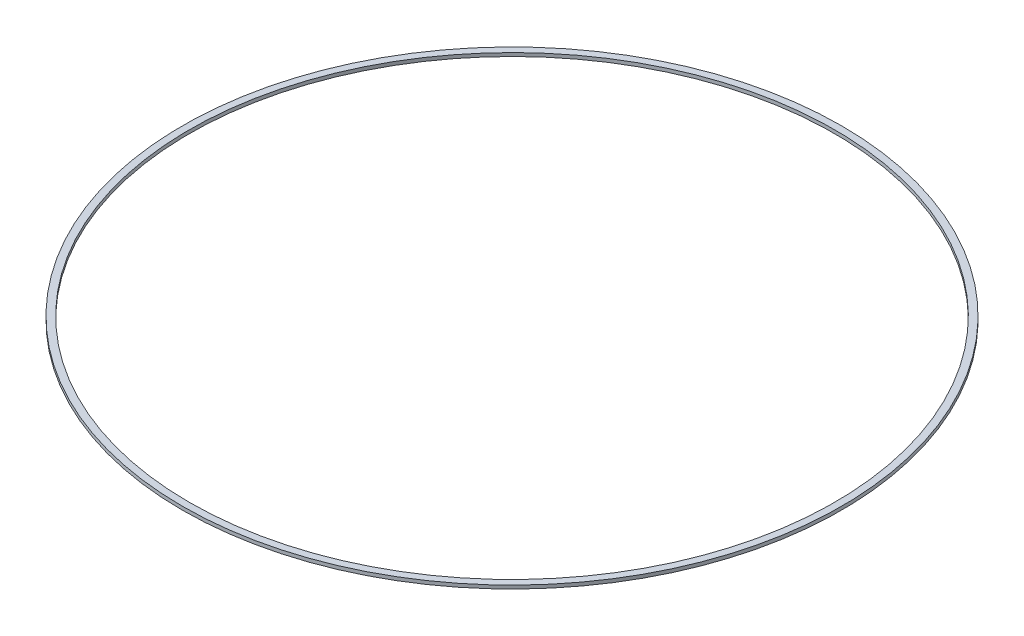
SolidWorks part; units mm, degrees
ref_plane "Front Plane" through (0, 0, 0) normal (0, 0, 1) x (1, 0, 0)
ref_plane "Top Plane" through (0, 0, 0) normal (0, 1, 0) x (1, 0, 0)
ref_plane "Right Plane" through (0, 0, 0) normal (1, 0, 0) x (0, 0, -1)
sketch "Sketch1" plane through (0, 0, 0) normal (0, 1, 0) x (1, 0, 0)
  circle A0 centre (-3.2216, 4.6022) radius 190
  circle A1 centre (-3.2216, 4.6022) radius 188
  circle A2 centre (-3.2216, 4.6022) radius 192
  dimension "D1" = 380
  dimension "D2" = 2
  dimension "D3" = 2
extrude "Boss-Extrude1" add sketch "Sketch1" along normal blind 2 contours A2 A0 | A0 A1
